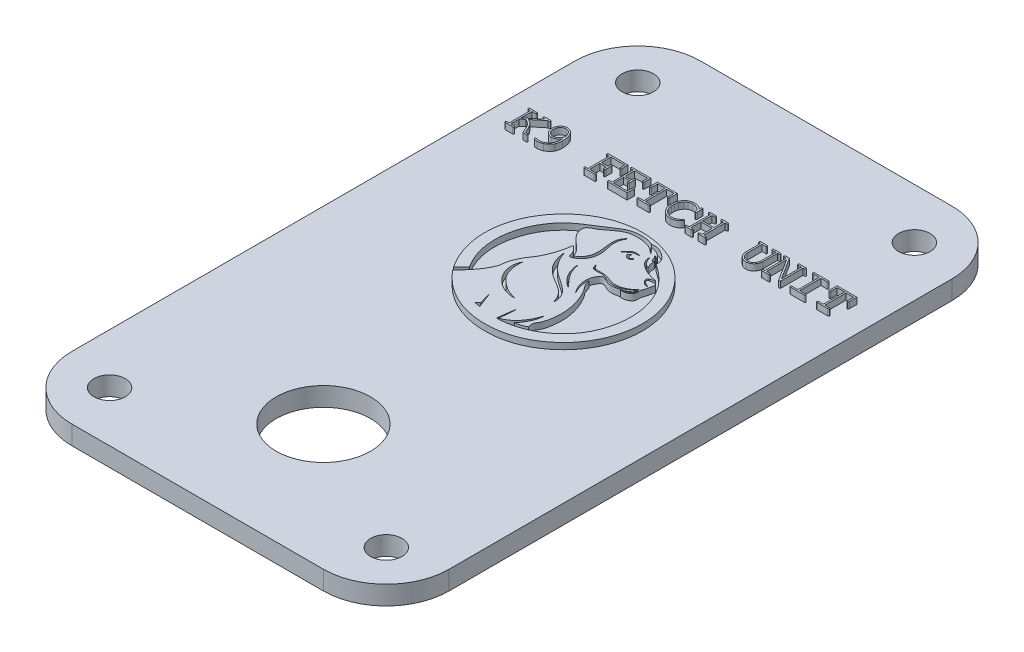
SolidWorks part; units mm, degrees
ref_plane "Alzado" through (0, 0, 0) normal (0, 0, 1) x (1, 0, 0)
ref_plane "Planta" through (0, 0, 0) normal (0, 1, 0) x (1, 0, 0)
ref_plane "Vista lateral" through (0, 0, 0) normal (1, 0, 0) x (0, 0, -1)
sketch "Croquis1" plane through (0, 0, 0) normal (0, 1, 0) x (1, 0, 0)
  line L0 (-30, 40) -> (-30, -40)
  line L1 (-20, -50) -> (20, -50)
  line L2 (30, -40) -> (30, 40)
  line L3 (20, 50) -> (-20, 50)
  arc A0 (-30, -40) -> (-20, -50) centre (-20, -40) ccw
  arc A1 (20, -50) -> (30, -40) centre (20, -40) ccw
  arc A2 (30, 40) -> (20, 50) centre (20, 40) ccw
  arc A3 (-20, 50) -> (-30, 40) centre (-20, 40) ccw
  point P6 (-30, -50)
  point P9 (30, -50)
  point P14 (-30, 50)
  point P16 (-30, 0)
  point P17 (0, -50)
  dimension "D3" = 60
  dimension "D1" = 10
  dimension "D2" = 100
extrude "Saliente-Extruir1" add sketch "Croquis1" along normal blind 3
sketch "Croquis2" plane through (0, 3, 0) normal (0, 1, 0) x (1, 0, 0)
  line L0 (-20, -50) -> (20, -50) construction
  circle A0 centre (0, -30) radius 7.5
  dimension "D1" = 15
  dimension "D2" = 20
extrude "Cortar-Extruir1" cut sketch "Croquis2" against normal up to next
sketch "Croquis3" plane through (0, 3, 0) normal (0, 1, 0) x (1, 0, 0)
  line L0 (-30, 40) -> (-30, -40) construction
  line L1 (20, 50) -> (-20, 50) construction
  line L2 (-20, -50) -> (20, -50) construction
  line L3 (30, -40) -> (30, 40) construction
  circle A0 centre (-22, 42) radius 2.5
  circle A1 centre (-22, -42) radius 2.5
  circle A2 centre (22, -42) radius 2.5
  circle A3 centre (22, 42) radius 2.5
  dimension "D3" = 5
  dimension "D1" = 8
  dimension "D2" = 8
  dimension "D4" = 8
  dimension "D5" = 8
extrude "Cortar-Extruir2" cut sketch "Croquis3" against normal up to next
sketch "Croquis4" plane through (0, 3, 0) normal (0, 1, 0) x (1, 0, 0)
  line L0 (-30, 25) -> (30, 25) construction
  line L1 (-30, 40) -> (-30, -40) construction
  line L2 (30, -40) -> (30, 40) construction
  line L3 (20, 50) -> (-20, 50) construction
  text T0 "K9 FETCH UNIT" font "Courier New" height in points 18
  dimension "D1" = 25
extrude "Saliente-Extruir2" add sketch "Croquis4" along normal blind 1
sketch "Croquis6" plane through (0, 3, 0) normal (0, 1, 0) x (1, 0, 0)
  line L0 (144.9222, 475.5065) -> (798.2555, 475.5065) construction
  line L1 (-10.2788, 0.9893) -> (-9.0414, 2.2809)
  line L2 (0.1722, -2.6044) -> (0.5118, 0)
  line L3 (0.5118, 0) -> (0.583, -0.0093)
  line L4 (0.583, -0.0093) -> (0.3635, -2.5026)
  line L5 (3.6249, 1.3314) -> (3.6924, 1.3314)
  line L6 (-3.7191, 0.1517) -> (-2.7545, -2.3893)
  line L7 (-2.7545, -2.3893) -> (-3.6361, -2.2183)
  line L8 (-3.6361, -2.2183) -> (-3.6361, -2.1113)
  line L9 (-3.6361, -2.1113) -> (-3.2368, -1.7121)
  line L10 (-3.2368, -1.7121) -> (-3.7191, 0.1517)
  spline S0 degree 3 poles (-10.2788, 0.9893) (-11.1741, 2.3378) (-12.7063, 5.709) (-12.5917, 11.7807) (-9.2059, 17.4463) (-4.2708, 20.3731) (0.4683, 20.948) (4.4527, 20.1843) (9.1077, 17.4869) (12.3039, 12.6111) (12.7664, 7.2148) (11.6025, 2.7089) (8.7202, -1.3694) (4.6013, -3.7872) (0.2187, -4.5462) (-4.9265, -3.9382) (-8.4106, -1.4166) (-9.9394, 0.5052) knots 0 0 0 0 0.062628 0.14021 0.224608 0.306676 0.352029 0.406793 0.460277 0.556708 0.617532 0.664857 0.73407 0.80482 0.842869 0.904699 1 1 1 1
  spline S1 degree 3 poles (-9.0414, 2.2809) (-9.7412, 3.3683) (-11.3098, 6.9198) (-10.4309, 12.5477) (-7.4276, 16.2146) (-4.8702, 17.804) (-3.2996, 18.7947) (-1.9479, 19.7346) (-1.0335, 20.1339) (0.5024, 20.3152) (1.5329, 20.1824) (2.2757, 19.881) knots 0 0 0 0 0.150884 0.444065 0.603654 0.689702 0.793754 0.82018 0.881806 0.907059 1 1 1 1
  spline S2 degree 3 poles (2.2757, 19.881) (2.5417, 19.8426) (2.9134, 19.9394) (3.3601, 19.829) (3.9842, 19.6279) (4.7718, 19.1453) (5.5057, 18.2809) (5.4566, 17.6656) (5.4708, 17.4487) knots 0 0 0 0 0.178569 0.241549 0.30284 0.613548 0.851188 1 1 1 1
  spline S3 degree 3 poles (5.4708, 17.4487) (6.4849, 16.7977) (8.3161, 15.3182) (11.287, 10.5255) (10.6299, 1.2279) (3.8265, -2.5914) (0.222, -2.642) knots 0 0 0 0 0.132041 0.253097 0.608068 1 1 1 1
  spline S4 degree 1 poles (0.222, -2.642) (0.1722, -2.6044) knots 0 0 1 1
  spline S5 degree 2 poles (0.3635, -2.5026) (2.7275, -1.5845) (3.6249, 1.3314) knots 0 0 0 1 1 1
  spline S6 degree 2 poles (3.6924, 1.3314) (3.5361, -0.4195) (2.2239, -1.825) knots 0 0 0 1 1 1
  spline S7 degree 2 poles (2.2239, -1.825) (3.1228, -1.7583) (3.94, -1.3022) knots 0 0 0 1 1 1
  spline S8 degree 3 poles (3.94, -1.3022) (3.8347, -0.9821) (3.7329, -0.4924) (4.0267, -0.0661) (4.3563, 0.448) (4.5328, 1.11) (4.7479, 2.4193) (4.7948, 3.9495) (4.2807, 6.263) (3.5099, 7.9553) (2.5975, 9.002) (2.3491, 10.4987) (2.3481, 8.8725) (2.5618, 8.1231) (2.7376, 7.5787) (2.9783, 7.2412) (2.907, 7.1873) (2.8845, 7.2387) knots 0 0 0 0 0.070772 0.086709 0.105069 0.196427 0.223424 0.378428 0.505261 0.712977 0.735736 0.808178 0.879882 0.919861 0.9911 0.993072 1 1 1 1
  spline S9 degree 3 poles (2.8845, 7.2387) (2.4407, 7.9025) (1.8299, 9.2677) (2.2286, 10.8683) (2.7876, 11.4633) (3.0414, 11.5024) (3.444, 11.4255) (3.8359, 11.1708) (4.6481, 10.9034) (5.5354, 10.9913) (6.7664, 11.3532) (7.5558, 11.7721) (7.7087, 12.3771) knots 0 0 0 0 0.241135 0.423813 0.455188 0.474606 0.497585 0.576625 0.611442 0.752118 0.830705 1 1 1 1
  spline S10 degree 3 poles (7.7087, 12.3771) (7.7628, 12.3742) (7.7405, 12.281) (7.7503, 12.2005) (7.7214, 11.9247) (7.2659, 11.4642) (6.8564, 11.2505) (5.9838, 11.0955) (6.4799, 11.0556) (6.7171, 11.0823) (7.2318, 11.199) (7.7244, 11.527) (7.8772, 12.1717) (7.7614, 12.6268) (7.9812, 13.0371) (8.0786, 13.3732) (8.1398, 13.8837) (8.3054, 14.2917) (8.2645, 14.5862) knots 0 0 0 0 0.019532 0.027723 0.037357 0.137321 0.267357 0.32044 0.365244 0.397867 0.439176 0.588978 0.616588 0.723429 0.777571 0.813064 0.87521 1 1 1 1
  spline S11 degree 3 poles (8.2645, 14.5862) (8.1782, 14.6933) (7.9058, 14.7273) (7.4931, 14.6883) (6.7255, 14.6291) (7.1299, 14.0538) (7.4169, 13.9166) (7.6166, 13.8232) (7.8037, 13.8161) (7.7976, 13.6889) (7.7407, 13.6804) (7.668, 13.6801) (7.5467, 13.6844) (7.2763, 13.8016) (6.9593, 14.0783) (6.686, 14.4487) (6.7473, 14.7635) (6.8588, 14.8072) (6.9019, 14.8389) knots 0 0 0 0 0.091336 0.158315 0.312318 0.419197 0.49443 0.535605 0.575583 0.590312 0.598914 0.610318 0.640918 0.678855 0.805962 0.926381 0.963809 1 1 1 1
  spline S12 degree 2 poles (6.9019, 14.8389) (7.2534, 15.0921) (7.7305, 15.0734) knots 0 0 0 1 1 1
  spline S13 degree 3 poles (7.7305, 15.0734) (7.6796, 15.1256) (7.5389, 15.172) (7.3256, 15.2135) (6.3964, 15.4344) (4.9592, 15.963) (3.9794, 17.0836) (4.0186, 17.7677) knots 0 0 0 0 0.043654 0.0883 0.133905 0.628462 1 1 1 1
  spline S14 degree 1 poles (4.0186, 17.7677) (4.0903, 17.7677) knots 0 0 1 1
  spline S15 degree 3 poles (4.0903, 17.7677) (4.0919, 17.6454) (4.3484, 17.0364) (4.7423, 16.5168) (5.3203, 16.3323) knots 0 0 0 0 0.185033 1 1 1 1
  spline S16 degree 2 poles (5.3203, 16.3323) (4.9085, 16.9293) (4.9739, 17.7234) knots 0 0 0 1 1 1
  spline S17 degree 3 poles (4.9739, 17.7234) (4.925, 17.6738) (4.8876, 17.5583) (4.759, 17.5426) (4.737, 17.5752) knots 0 0 0 0 0.66996 1 1 1 1
  spline S18 degree 3 poles (4.737, 17.5752) (4.4705, 17.7439) (4.5317, 18.2533) (4.2202, 18.4503) (4.1729, 18.5488) (4.2319, 18.5822) (4.2724, 18.5519) (4.2996, 18.5389) knots 0 0 0 0 0.706005 0.869248 0.898195 0.923189 1 1 1 1
  spline S19 degree 2 poles (4.2996, 18.5389) (4.7007, 18.3) (4.9209, 17.8629) knots 0 0 0 1 1 1
  spline S20 degree 3 poles (4.9209, 17.8629) (4.9489, 18.0688) (4.7105, 18.3805) (4.1065, 19.0956) (3.3042, 19.3899) (2.7005, 19.3833) knots 0 0 0 0 0.214935 0.357726 1 1 1 1
  spline S21 degree 2 poles (2.7005, 19.3833) (3.2034, 19.0802) (3.5308, 18.5656) knots 0 0 0 1 1 1
  spline S22 degree 3 poles (3.5308, 18.5656) (3.5785, 18.4288) (3.1927, 18.8015) (3.1421, 18.8191) (2.9509, 19.0085) knots 0 0 0 0 0.328298 1 1 1 1
  spline S23 degree 3 poles (2.9509, 19.0085) (2.2269, 19.4894) (0.8481, 19.7606) (-0.4643, 19.6816) (-0.9126, 19.6056) knots 0 0 0 0 0.656873 1 1 1 1
  spline S24 degree 3 poles (-0.9126, 19.6056) (-1.2774, 19.5025) (-2.0204, 19.1271) (-3.1007, 18.3298) (-4.1012, 17.5137) (-5.8227, 16.8104) (-4.9895, 15.1436) (-4.6171, 14.834) knots 0 0 0 0 0.155635 0.33963 0.546182 0.707597 1 1 1 1
  spline S25 degree 3 poles (-4.6171, 14.834) (-3.8699, 13.8624) (-2.6131, 13.3598) (-2.2766, 12.0468) knots 0 0 0 0 1 1 1 1
  spline S26 degree 3 poles (-2.2766, 12.0468) (-1.6931, 12.2696) (-0.7481, 13.4778) (-0.8809, 15.9512) (-1.3173, 17.7828) (-0.3737, 18.6777) knots 0 0 0 0 0.257176 0.550106 1 1 1 1
  spline S27 degree 1 poles (-0.3737, 18.6777) (-0.3757, 18.5123) knots 0 0 1 1
  spline S28 degree 3 poles (-0.3757, 18.5123) (-0.8108, 17.9093) (-0.8737, 16.8372) (-0.4849, 15.4117) (-0.191, 13.5386) (-1.2506, 11.8962) (-2.3975, 11.6446) knots 0 0 0 0 0.285614 0.364562 0.574509 1 1 1 1
  spline S29 degree 3 poles (-2.3975, 11.6446) (-2.5594, 11.5957) (-2.6881, 11.893) (-2.7857, 12.6266) (-3.3091, 13.1957) (-3.7191, 13.4326) knots 0 0 0 0 0.172814 0.337171 1 1 1 1
  spline S30 degree 3 poles (-3.7191, 13.4326) (-3.8273, 12.3895) (-4.2606, 10.8152) (-5.0153, 9.171) (-5.7461, 8.1754) (-6.383, 7.0984) (-6.7838, 5.9379) (-6.831, 4.9302) (-7.0571, 4.4016) (-7.8292, 2.7065) (-8.9409, 1.4962) (-9.9394, 0.5052) knots 0 0 0 0 0.215563 0.33256 0.369234 0.469199 0.589652 0.616062 0.675625 0.705502 1 1 1 1
  spline S31 degree 3 poles (1.873, 17.2658) (0.6723, 16.0411) (1.3215, 16.9491) (1.8859, 17.4669) (2.4842, 17.4404) (3.1246, 17.3617) (2.7294, 17.2669) (2.4811, 17.2818) (1.873, 17.2658) (0.6723, 16.0411) (1.3215, 16.9491) knots -0.429258 -0.400069 -0.31069 0 0.038227 0.332512 0.435419 0.514271 0.570742 0.599931 0.68931 1 1.038227 1.332512 1.435419 only from (0.963, 16.4433) to (0.963, 16.4433)
  spline S32 degree 3 poles (1.941, 16.1982) (1.8169, 16.4624) (1.9786, 16.6045) (2.2485, 16.9872) (2.1937, 16.5238) (2.2731, 16.335) (2.4866, 16.1574) (2.7417, 16.2882) (2.8739, 16.5343) (2.9832, 16.3418) (2.8911, 16.1777) (2.6591, 15.9975) (2.2272, 15.9787) (1.941, 16.1982) (1.8169, 16.4624) (1.9786, 16.6045) knots -0.331247 -0.194605 -0.052858 0 0.023076 0.141771 0.240555 0.282522 0.341828 0.468059 0.497457 0.545154 0.588893 0.668753 0.805395 0.947142 1 1.023076 1.141771 1.240555 only from (1.8515, 16.4807) to (1.8515, 16.4807)
  spline S33 degree 3 poles (3.1761, 11.8873) (3.6093, 11.7712) (5.0528, 10.9935) (6.8577, 11.7541) (7.5597, 12.6218) knots 0 0 0 0 0.282438 1 1 1 1
  spline S34 degree 2 poles (7.5597, 12.6218) (7.6533, 12.6767) (7.6323, 12.4878) knots 0 0 0 1 1 1
  spline S35 degree 3 poles (7.6323, 12.4878) (7.3803, 12.1542) (6.7314, 11.6803) (5.5122, 11.0925) (4.2671, 11.2037) (3.3214, 11.5357) (2.8498, 11.747) (1.8818, 11.9016) (0.8756, 11.4256) (0.7622, 12.5789) knots 0 0 0 0 0.161518 0.305112 0.515838 0.619728 0.695713 0.713228 1 1 1 1
  spline S36 degree 2 poles (0.7622, 12.5789) (0.822, 12.6325) (0.8464, 12.5073) knots 0 0 0 1 1 1
  spline S37 degree 3 poles (0.8464, 12.5073) (0.9328, 12.2494) (1.2434, 11.9543) (1.65, 11.9627) (2.2224, 11.946) (2.7376, 12.0133) (3.1761, 11.8873) knots 0 0 0 0 0.323669 0.393821 0.477746 1 1 1 1
  spline S38 degree 3 poles (-0.5793, 11.133) (-0.5751, 9.6467) (0.726, 8.2422) (1.6381, 7.3493) knots 0 0 0 0 1 1 1 1
  spline S39 degree 2 poles (1.6381, 7.3493) (1.5786, 7.2862) (1.4958, 7.3716) knots 0 0 0 1 1 1
  spline S40 degree 3 poles (1.4958, 7.3716) (0.7276, 7.8915) (-0.3021, 9.0144) (-0.6121, 10.4892) (-0.7054, 11.0656) (-0.5793, 11.133) knots 0 0 0 0 0.620795 0.93415 1 1 1 1
  spline S41 degree 3 poles (-3.4252, 11.8293) (-3.3856, 10.7835) (-2.7854, 8.9125) (-0.1229, 6.8562) (2.0097, 6.0052) (2.402, 4.272) knots 0 0 0 0 0.31912 0.549517 1 1 1 1
  spline S42 degree 1 poles (2.402, 4.272) (2.5308, 4.2157) knots 0 0 1 1
  spline S43 degree 3 poles (2.5308, 4.2157) (2.5277, 4.8285) (2.1888, 6.0025) (0.539, 7.3571) (-1.8383, 8.6844) (-3.0988, 10.6309) (-3.4252, 11.8293) knots 0 0 0 0 0.185205 0.341347 0.626788 1 1 1 1
  spline S44 degree 3 poles (-5.4591, 7.161) (-5.794, 6.6178) (-6.1228, 3.6819) (-3.3721, 1.4658) (-1.1694, 1.5663) knots 0 0 0 0 0.232529 1 1 1 1
  spline S45 degree 3 poles (-1.1694, 1.5663) (-1.6228, 1.7169) (-2.5754, 1.9634) (-3.721, 2.7795) (-5.3258, 4.1857) (-5.6155, 6.0128) (-5.4591, 7.161) knots 0 0 0 0 0.18486 0.374832 0.537658 1 1 1 1
extrude "Saliente-Extruir3" add sketch "Croquis6" along normal blind 1
